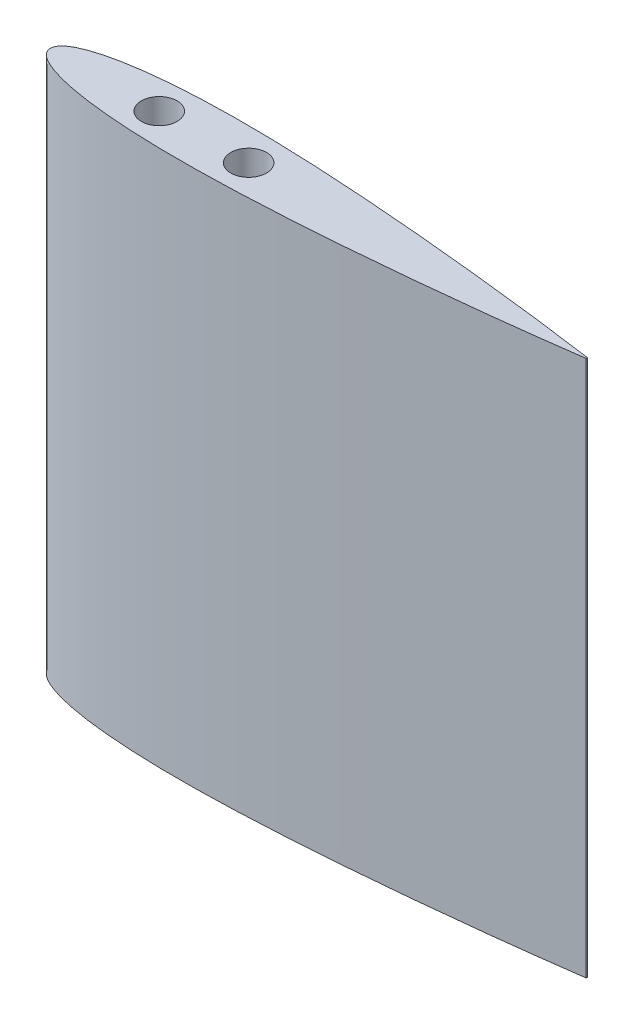
SolidWorks part; units mm, degrees
material "ABS"
ref_plane "Front Plane" through (0, 0, 0) normal (0, 0, 1) x (1, 0, 0)
ref_plane "Top Plane" through (0, 0, 0) normal (0, 1, 0) x (1, 0, 0)
ref_plane "Right Plane" through (0, 0, 0) normal (1, 0, 0) x (0, 0, -1)
curve "Curve3"
  spline degree 3 poles (25.4, 0, 0.032) (25.3951, 0, 0.0327) (25.3753, 0, 0.0355) (25.3309, 0, 0.0417) (25.257, 0, 0.052) (25.1537, 0, 0.0664) (25.0214, 0, 0.0846) (24.8603, 0, 0.1068) (24.6708, 0, 0.1326) (24.4533, 0, 0.1619) (24.2084, 0, 0.1946) (23.9366, 0, 0.2304) (23.6385, 0, 0.2691) (23.3149, 0, 0.3106) (22.9666, 0, 0.3545) (22.5942, 0, 0.4008) (22.1987, 0, 0.449) (21.7811, 0, 0.499) (21.3422, 0, 0.5505) (20.8832, 0, 0.6032) (20.405, 0, 0.6571) (19.9089, 0, 0.7116) (19.3959, 0, 0.7667) (18.8673, 0, 0.8219) (18.3242, 0, 0.8772) (17.7681, 0, 0.9321) (17.2001, 0, 0.9864) (16.6216, 0, 1.0399) (16.0339, 0, 1.0922) (15.4384, 0, 1.143) (14.8366, 0, 1.1921) (14.2297, 0, 1.2391) (13.6193, 0, 1.2836) (13.0067, 0, 1.3254) (12.3935, 0, 1.3642) (11.7809, 0, 1.3995) (11.1705, 0, 1.4311) (10.5636, 0, 1.4587) (9.9618, 0, 1.4818) (9.3663, 0, 1.5004) (8.7786, 0, 1.514) (8.2001, 0, 1.5224) (7.632, 0, 1.5254) (7.0758, 0, 1.5227) (6.5327, 0, 1.5144) (6.0041, 0, 1.5) (5.491, 0, 1.4798) (4.9948, 0, 1.4535) (4.5166, 0, 1.4212) (4.0575, 0, 1.3829) (3.6185, 0, 1.3388) (3.2008, 0, 1.2888) (2.8052, 0, 1.2334) (2.4327, 0, 1.1725) (2.0841, 0, 1.1064) (1.7603, 0, 1.0355) (1.462, 0, 0.96) (1.1898, 0, 0.8801) (0.9445, 0, 0.7962) (0.7264, 0, 0.7086) (0.536, 0, 0.6175) (0.3737, 0, 0.523) (0.2396, 0, 0.4254) (0.1341, 0, 0.3245) (0.0574, 0, 0.22) (0.0105, 0, 0.1114) (-0.0051, 0, 0) (0.0105, 0, -0.1114) (0.0574, 0, -0.22) (0.1341, 0, -0.3245) (0.2396, 0, -0.4254) (0.3737, 0, -0.523) (0.536, 0, -0.6175) (0.7264, 0, -0.7086) (0.9445, 0, -0.7962) (1.1898, 0, -0.8801) (1.462, 0, -0.96) (1.7603, 0, -1.0355) (2.0841, 0, -1.1064) (2.4327, 0, -1.1725) (2.8052, 0, -1.2334) (3.2008, 0, -1.2888) (3.6185, 0, -1.3388) (4.0575, 0, -1.3829) (4.5166, 0, -1.4212) (4.9948, 0, -1.4535) (5.491, 0, -1.4798) (6.0041, 0, -1.5) (6.5327, 0, -1.5144) (7.0758, 0, -1.5227) (7.632, 0, -1.5254) (8.2001, 0, -1.5224) (8.7786, 0, -1.514) (9.3663, 0, -1.5004) (9.9618, 0, -1.4818) (10.5636, 0, -1.4587) (11.1705, 0, -1.4311) (11.7809, 0, -1.3995) (12.3935, 0, -1.3642) (13.0067, 0, -1.3254) (13.6193, 0, -1.2836) (14.2297, 0, -1.2391) (14.8366, 0, -1.1921) (15.4384, 0, -1.143) (16.0339, 0, -1.0922) (16.6216, 0, -1.0399) (17.2001, 0, -0.9864) (17.7681, 0, -0.9321) (18.3242, 0, -0.8772) (18.8673, 0, -0.8219) (19.3959, 0, -0.7667) (19.9089, 0, -0.7116) (20.405, 0, -0.6571) (20.8832, 0, -0.6032) (21.3422, 0, -0.5505) (21.7811, 0, -0.499) (22.1987, 0, -0.449) (22.5942, 0, -0.4008) (22.9666, 0, -0.3545) (23.3149, 0, -0.3106) (23.6385, 0, -0.2691) (23.9366, 0, -0.2304) (24.2084, 0, -0.1946) (24.4533, 0, -0.1619) (24.6708, 0, -0.1326) (24.8603, 0, -0.1068) (25.0214, 0, -0.0846) (25.1537, 0, -0.0664) (25.257, 0, -0.052) (25.3309, 0, -0.0417) (25.3753, 0, -0.0355) (25.3951, 0, -0.0327) (25.4, 0, -0.032) knots 0 0 0 0 0.000289 0.001156 0.002598 0.004612 0.007194 0.010336 0.014031 0.018272 0.023046 0.028343 0.03415 0.040454 0.047238 0.054489 0.062187 0.070314 0.078852 0.08778 0.097078 0.106722 0.116691 0.126961 0.137507 0.148306 0.159331 0.170556 0.181957 0.193504 0.205171 0.216932 0.228758 0.240621 0.252495 0.26435 0.276161 0.287898 0.299536 0.311047 0.322405 0.333584 0.344559 0.355306 0.3658 0.376018 0.385937 0.395538 0.404798 0.413699 0.422221 0.430349 0.438066 0.445357 0.452209 0.458612 0.464554 0.47003 0.475035 0.479569 0.483637 0.48725 0.490431 0.493219 0.495674 0.497891 0.5 0.502109 0.504326 0.506781 0.509569 0.51275 0.516363 0.520431 0.524965 0.52997 0.535446 0.541388 0.547791 0.554643 0.561934 0.569651 0.577779 0.586301 0.595202 0.604462 0.614063 0.623982 0.6342 0.644694 0.655441 0.666416 0.677595 0.688953 0.700464 0.712102 0.723839 0.73565 0.747505 0.759379 0.771242 0.783068 0.794829 0.806496 0.818043 0.829444 0.840669 0.851694 0.862493 0.873039 0.883309 0.893278 0.902922 0.91222 0.921148 0.929686 0.937813 0.945511 0.952762 0.959546 0.96585 0.971657 0.976954 0.981728 0.985969 0.989664 0.992806 0.995388 0.997402 0.998844 0.999711 1 1 1 1
sketch "Sketch3" plane through (0, 0, 0) normal (0, 1, 0) x (1, 0, 0)
  line L1 (76.2, 0) -> (0, 0) construction
  line L2 (76.199, 0.048) -> (76.199, -0.048)
  spline S1 degree 3 poles (76.199, -0.048) (76.1915, -0.049) (76.1619, -0.0532) (76.0436, -0.0698) (75.8665, -0.0945) (75.631, -0.127) (75.3894, -0.1602) (75.1051, -0.1989) (74.7789, -0.2429) (74.4115, -0.2919) (74.0038, -0.3456) (73.5568, -0.4037) (73.0714, -0.4659) (72.351, -0.5568) (71.5835, -0.6511) (70.7706, -0.7484) (70.1123, -0.8257) (69.4237, -0.9049) (68.7065, -0.9856) (67.9623, -1.0674) (67.1928, -1.15) (66.3999, -1.2328) (65.5853, -1.3157) (64.7511, -1.3981) (63.8991, -1.4797) (63.0313, -1.5598) (62.1498, -1.6383) (61.2566, -1.7146) (60.3538, -1.7882) (59.4435, -1.8586) (58.5279, -1.9254) (57.6091, -1.9882) (56.6892, -2.0463) (55.4668, -2.1168) (54.25, -2.1762) (52.7477, -2.2341) (51.5649, -2.2666) (50.399, -2.2836) (49.547, -2.288) (48.7127, -2.2841) (47.8981, -2.2716) (47.1051, -2.2501) (46.3355, -2.2197) (45.5912, -2.1802) (44.8739, -2.1318) (44.1852, -2.0744) (43.5268, -2.0081) (42.9001, -1.9332) (42.3067, -1.8501) (41.748, -1.7587) (41.2251, -1.6597) (40.7394, -1.5533) (40.292, -1.44) (39.8837, -1.3202) (39.5156, -1.1944) (39.1885, -1.0629) (38.9029, -0.9262) (38.6595, -0.7845) (38.4584, -0.6381) (38.3001, -0.4868) (38.185, -0.33) (38.1147, -0.1671) (38.0913, 0) (38.1147, 0.1671) (38.185, 0.33) (38.3001, 0.4868) (38.4584, 0.6381) (38.6595, 0.7845) (38.9029, 0.9262) (39.1885, 1.0629) (39.5156, 1.1944) (39.8837, 1.3202) (40.292, 1.44) (40.7394, 1.5533) (41.2251, 1.6597) (41.748, 1.7587) (42.3067, 1.8501) (42.9001, 1.9332) (43.5268, 2.0081) (44.1852, 2.0744) (44.8739, 2.1318) (45.5912, 2.1802) (46.3355, 2.2197) (47.1051, 2.2501) (47.8981, 2.2716) (48.7127, 2.2841) (49.547, 2.288) (50.399, 2.2836) (51.5649, 2.2666) (53.0515, 2.2257) (54.5537, 2.1623) (55.7703, 2.0993) (56.6892, 2.0463) (57.6091, 1.9882) (58.5279, 1.9254) (59.4435, 1.8586) (60.3538, 1.7882) (61.2566, 1.7146) (62.1498, 1.6383) (63.0313, 1.5598) (63.8991, 1.4797) (64.7511, 1.3981) (65.5853, 1.3157) (66.3999, 1.2328) (67.1928, 1.15) (67.9623, 1.0674) (68.7065, 0.9856) (69.4237, 0.9049) (70.1123, 0.8257) (70.7706, 0.7484) (71.5835, 0.6511) (72.351, 0.5568) (73.0714, 0.4659) (73.5568, 0.4037) (74.0038, 0.3456) (74.4115, 0.2919) (74.7789, 0.2429) (75.1051, 0.1989) (75.3894, 0.1602) (75.631, 0.127) (75.8665, 0.0945) (76.0436, 0.0698) (76.1619, 0.0532) (76.1915, 0.049) (76.199, 0.048) knots 0 0 0 0 0.000289 0.001156 0.004612 0.007194 0.010336 0.014031 0.018272 0.023046 0.028343 0.03415 0.040454 0.047238 0.062187 0.070314 0.078852 0.08778 0.097078 0.106722 0.116691 0.126961 0.137507 0.148306 0.159331 0.170556 0.181957 0.193504 0.205171 0.216932 0.228758 0.240621 0.252495 0.26435 0.287898 0.299536 0.322405 0.333584 0.344559 0.355306 0.3658 0.376018 0.385937 0.395538 0.404798 0.413699 0.422221 0.430349 0.438066 0.445357 0.452209 0.458612 0.464554 0.47003 0.475035 0.479569 0.483637 0.48725 0.490431 0.493219 0.495674 0.497891 0.5 0.502109 0.504326 0.506781 0.509569 0.51275 0.516363 0.520431 0.524965 0.52997 0.535446 0.541388 0.547791 0.554643 0.561934 0.569651 0.577779 0.586301 0.595202 0.604462 0.614063 0.623982 0.6342 0.644694 0.655441 0.666416 0.677595 0.700464 0.723839 0.73565 0.747505 0.759379 0.771242 0.783068 0.794829 0.806496 0.818043 0.829444 0.840669 0.851694 0.862493 0.873039 0.883309 0.893278 0.902922 0.91222 0.921148 0.929686 0.937813 0.952762 0.959546 0.96585 0.971657 0.976954 0.981728 0.985969 0.989664 0.992806 0.995388 0.998844 0.999711 1 1 1 1
  point P2 (76.1996, 0.0521)
  point P7 (76.2069, -0.048)
sketch "Sketch4" plane through (0, 0, 0) normal (0, 0, 1) x (1, 0, 0)
  line L0 (76.2, 0) -> (76.2, 43.9941)
  line L1 (76.199, 0) -> (38.099, 0) construction
  line L2 (76.2, 43.9941) -> (38.1, 43.9941) construction
  line L3 (0, 0) -> (38.1, 43.9941)
  line L4 (0, 0) -> (76.2, 0) construction
  dimension "D1" = 43.9941
  dimension "D2" = 38.1
ref_plane "Plane1" through (0, 43.9941, 0) normal (0, 1, 0) x (1, 0, 0)
curve "Curve4"
  spline degree 3 poles (25.4, 0, 0.032) (25.3951, 0, 0.0327) (25.3753, 0, 0.0355) (25.3309, 0, 0.0417) (25.257, 0, 0.052) (25.1537, 0, 0.0664) (25.0214, 0, 0.0846) (24.8603, 0, 0.1068) (24.6708, 0, 0.1326) (24.4533, 0, 0.1619) (24.2084, 0, 0.1946) (23.9366, 0, 0.2304) (23.6385, 0, 0.2691) (23.3149, 0, 0.3106) (22.9666, 0, 0.3545) (22.5942, 0, 0.4008) (22.1987, 0, 0.449) (21.7811, 0, 0.499) (21.3422, 0, 0.5505) (20.8832, 0, 0.6032) (20.405, 0, 0.6571) (19.9089, 0, 0.7116) (19.3959, 0, 0.7667) (18.8673, 0, 0.8219) (18.3242, 0, 0.8772) (17.7681, 0, 0.9321) (17.2001, 0, 0.9864) (16.6216, 0, 1.0399) (16.0339, 0, 1.0922) (15.4384, 0, 1.143) (14.8366, 0, 1.1921) (14.2297, 0, 1.2391) (13.6193, 0, 1.2836) (13.0067, 0, 1.3254) (12.3935, 0, 1.3642) (11.7809, 0, 1.3995) (11.1705, 0, 1.4311) (10.5636, 0, 1.4587) (9.9618, 0, 1.4818) (9.3663, 0, 1.5004) (8.7786, 0, 1.514) (8.2001, 0, 1.5224) (7.632, 0, 1.5254) (7.0758, 0, 1.5227) (6.5327, 0, 1.5144) (6.0041, 0, 1.5) (5.491, 0, 1.4798) (4.9948, 0, 1.4535) (4.5166, 0, 1.4212) (4.0575, 0, 1.3829) (3.6185, 0, 1.3388) (3.2008, 0, 1.2888) (2.8052, 0, 1.2334) (2.4327, 0, 1.1725) (2.0841, 0, 1.1064) (1.7603, 0, 1.0355) (1.462, 0, 0.96) (1.1898, 0, 0.8801) (0.9445, 0, 0.7962) (0.7264, 0, 0.7086) (0.536, 0, 0.6175) (0.3737, 0, 0.523) (0.2396, 0, 0.4254) (0.1341, 0, 0.3245) (0.0574, 0, 0.22) (0.0105, 0, 0.1114) (-0.0051, 0, 0) (0.0105, 0, -0.1114) (0.0574, 0, -0.22) (0.1341, 0, -0.3245) (0.2396, 0, -0.4254) (0.3737, 0, -0.523) (0.536, 0, -0.6175) (0.7264, 0, -0.7086) (0.9445, 0, -0.7962) (1.1898, 0, -0.8801) (1.462, 0, -0.96) (1.7603, 0, -1.0355) (2.0841, 0, -1.1064) (2.4327, 0, -1.1725) (2.8052, 0, -1.2334) (3.2008, 0, -1.2888) (3.6185, 0, -1.3388) (4.0575, 0, -1.3829) (4.5166, 0, -1.4212) (4.9948, 0, -1.4535) (5.491, 0, -1.4798) (6.0041, 0, -1.5) (6.5327, 0, -1.5144) (7.0758, 0, -1.5227) (7.632, 0, -1.5254) (8.2001, 0, -1.5224) (8.7786, 0, -1.514) (9.3663, 0, -1.5004) (9.9618, 0, -1.4818) (10.5636, 0, -1.4587) (11.1705, 0, -1.4311) (11.7809, 0, -1.3995) (12.3935, 0, -1.3642) (13.0067, 0, -1.3254) (13.6193, 0, -1.2836) (14.2297, 0, -1.2391) (14.8366, 0, -1.1921) (15.4384, 0, -1.143) (16.0339, 0, -1.0922) (16.6216, 0, -1.0399) (17.2001, 0, -0.9864) (17.7681, 0, -0.9321) (18.3242, 0, -0.8772) (18.8673, 0, -0.8219) (19.3959, 0, -0.7667) (19.9089, 0, -0.7116) (20.405, 0, -0.6571) (20.8832, 0, -0.6032) (21.3422, 0, -0.5505) (21.7811, 0, -0.499) (22.1987, 0, -0.449) (22.5942, 0, -0.4008) (22.9666, 0, -0.3545) (23.3149, 0, -0.3106) (23.6385, 0, -0.2691) (23.9366, 0, -0.2304) (24.2084, 0, -0.1946) (24.4533, 0, -0.1619) (24.6708, 0, -0.1326) (24.8603, 0, -0.1068) (25.0214, 0, -0.0846) (25.1537, 0, -0.0664) (25.257, 0, -0.052) (25.3309, 0, -0.0417) (25.3753, 0, -0.0355) (25.3951, 0, -0.0327) (25.4, 0, -0.032) knots 0 0 0 0 0.000289 0.001156 0.002598 0.004612 0.007194 0.010336 0.014031 0.018272 0.023046 0.028343 0.03415 0.040454 0.047238 0.054489 0.062187 0.070314 0.078852 0.08778 0.097078 0.106722 0.116691 0.126961 0.137507 0.148306 0.159331 0.170556 0.181957 0.193504 0.205171 0.216932 0.228758 0.240621 0.252495 0.26435 0.276161 0.287898 0.299536 0.311047 0.322405 0.333584 0.344559 0.355306 0.3658 0.376018 0.385937 0.395538 0.404798 0.413699 0.422221 0.430349 0.438066 0.445357 0.452209 0.458612 0.464554 0.47003 0.475035 0.479569 0.483637 0.48725 0.490431 0.493219 0.495674 0.497891 0.5 0.502109 0.504326 0.506781 0.509569 0.51275 0.516363 0.520431 0.524965 0.52997 0.535446 0.541388 0.547791 0.554643 0.561934 0.569651 0.577779 0.586301 0.595202 0.604462 0.614063 0.623982 0.6342 0.644694 0.655441 0.666416 0.677595 0.688953 0.700464 0.712102 0.723839 0.73565 0.747505 0.759379 0.771242 0.783068 0.794829 0.806496 0.818043 0.829444 0.840669 0.851694 0.862493 0.873039 0.883309 0.893278 0.902922 0.91222 0.921148 0.929686 0.937813 0.945511 0.952762 0.959546 0.96585 0.971657 0.976954 0.981728 0.985969 0.989664 0.992806 0.995388 0.997402 0.998844 0.999711 1 1 1 1
sketch "Sketch5" plane through (0, 43.9941, 0) normal (0, 1, 0) x (1, 0, 0)
  line L1 (76.2, 0) -> (38.1, 0) construction
  line L2 (76.2, 0) -> (0, 0) construction
  line L3 (76.2, 0.048) -> (76.2, -0.048)
  spline S1 degree 3 poles (76.2, -0.048) (76.1926, -0.049) (76.1629, -0.0532) (76.0446, -0.0698) (75.8676, -0.0945) (75.6321, -0.127) (75.3904, -0.1602) (75.1061, -0.1989) (74.7799, -0.2429) (74.4125, -0.2919) (74.0049, -0.3456) (73.5578, -0.4037) (73.0724, -0.4659) (72.3521, -0.5568) (71.5845, -0.6511) (70.7716, -0.7484) (70.1134, -0.8257) (69.4248, -0.9049) (68.7075, -0.9856) (67.9633, -1.0674) (67.1938, -1.15) (66.4009, -1.2328) (65.5864, -1.3157) (64.7521, -1.3981) (63.9001, -1.4797) (63.0323, -1.5598) (62.1508, -1.6383) (61.2576, -1.7146) (60.3549, -1.7882) (59.4446, -1.8586) (58.529, -1.9254) (57.6101, -1.9882) (56.6902, -2.0463) (55.4679, -2.1168) (54.2511, -2.1762) (52.7487, -2.2341) (51.566, -2.2666) (50.4001, -2.2836) (49.548, -2.288) (48.7137, -2.2841) (47.8991, -2.2716) (47.1061, -2.2501) (46.3366, -2.2197) (45.5922, -2.1802) (44.8749, -2.1318) (44.1862, -2.0744) (43.5278, -2.0081) (42.9012, -1.9332) (42.3078, -1.8501) (41.749, -1.7587) (41.2262, -1.6597) (40.7405, -1.5533) (40.293, -1.44) (39.8848, -1.3202) (39.5167, -1.1944) (39.1895, -1.0629) (38.904, -0.9262) (38.6605, -0.7845) (38.4594, -0.6381) (38.3012, -0.4868) (38.1861, -0.33) (38.1157, -0.1671) (38.0923, 0) (38.1157, 0.1671) (38.1861, 0.33) (38.3012, 0.4868) (38.4594, 0.6381) (38.6605, 0.7845) (38.904, 0.9262) (39.1895, 1.0629) (39.5167, 1.1944) (39.8848, 1.3202) (40.293, 1.44) (40.7405, 1.5533) (41.2262, 1.6597) (41.749, 1.7587) (42.3078, 1.8501) (42.9012, 1.9332) (43.5278, 2.0081) (44.1862, 2.0744) (44.8749, 2.1318) (45.5922, 2.1802) (46.3366, 2.2197) (47.1061, 2.2501) (47.8991, 2.2716) (48.7137, 2.2841) (49.548, 2.288) (50.4001, 2.2836) (51.566, 2.2666) (53.0526, 2.2257) (54.5547, 2.1623) (55.7713, 2.0993) (56.6902, 2.0463) (57.6101, 1.9882) (58.529, 1.9254) (59.4446, 1.8586) (60.3549, 1.7882) (61.2576, 1.7146) (62.1508, 1.6383) (63.0323, 1.5598) (63.9001, 1.4797) (64.7521, 1.3981) (65.5864, 1.3157) (66.4009, 1.2328) (67.1938, 1.15) (67.9633, 1.0674) (68.7075, 0.9856) (69.4248, 0.9049) (70.1134, 0.8257) (70.7716, 0.7484) (71.5845, 0.6511) (72.3521, 0.5568) (73.0724, 0.4659) (73.5578, 0.4037) (74.0049, 0.3456) (74.4125, 0.2919) (74.7799, 0.2429) (75.1061, 0.1989) (75.3904, 0.1602) (75.6321, 0.127) (75.8676, 0.0945) (76.0446, 0.0698) (76.1629, 0.0532) (76.1926, 0.049) (76.2, 0.048) knots 0 0 0 0 0.000289 0.001156 0.004612 0.007194 0.010336 0.014031 0.018272 0.023046 0.028343 0.03415 0.040454 0.047238 0.062187 0.070314 0.078852 0.08778 0.097078 0.106722 0.116691 0.126961 0.137507 0.148306 0.159331 0.170556 0.181957 0.193504 0.205171 0.216932 0.228758 0.240621 0.252495 0.26435 0.287898 0.299536 0.322405 0.333584 0.344559 0.355306 0.3658 0.376018 0.385937 0.395538 0.404798 0.413699 0.422221 0.430349 0.438066 0.445357 0.452209 0.458612 0.464554 0.47003 0.475035 0.479569 0.483637 0.48725 0.490431 0.493219 0.495674 0.497891 0.5 0.502109 0.504326 0.506781 0.509569 0.51275 0.516363 0.520431 0.524965 0.52997 0.535446 0.541388 0.547791 0.554643 0.561934 0.569651 0.577779 0.586301 0.595202 0.604462 0.614063 0.623982 0.6342 0.644694 0.655441 0.666416 0.677595 0.700464 0.723839 0.73565 0.747505 0.759379 0.771242 0.783068 0.794829 0.806496 0.818043 0.829444 0.840669 0.851694 0.862493 0.873039 0.883309 0.893278 0.902922 0.91222 0.921148 0.929686 0.937813 0.952762 0.959546 0.96585 0.971657 0.976954 0.981728 0.985969 0.989664 0.992806 0.995388 0.998844 0.999711 1 1 1 1
  dimension "D1" = 38.1
extrude "Boss-Extrude1" add sketch "Sketch3" along normal blind 38.1
sketch "Sketch6" plane through (0, 38.1, 0) normal (0, 1, 0) x (1, 0, 0)
  circle A0 centre (45.8305, 0) radius 1.27
  circle A1 centre (52.1805, 0) radius 1.27
  point P4 (0, 0)
  dimension "D1" = 2.54
  dimension "D2" = 6.35
extrude "Cut-Extrude1" cut sketch "Sketch6" against normal blind 12.7
